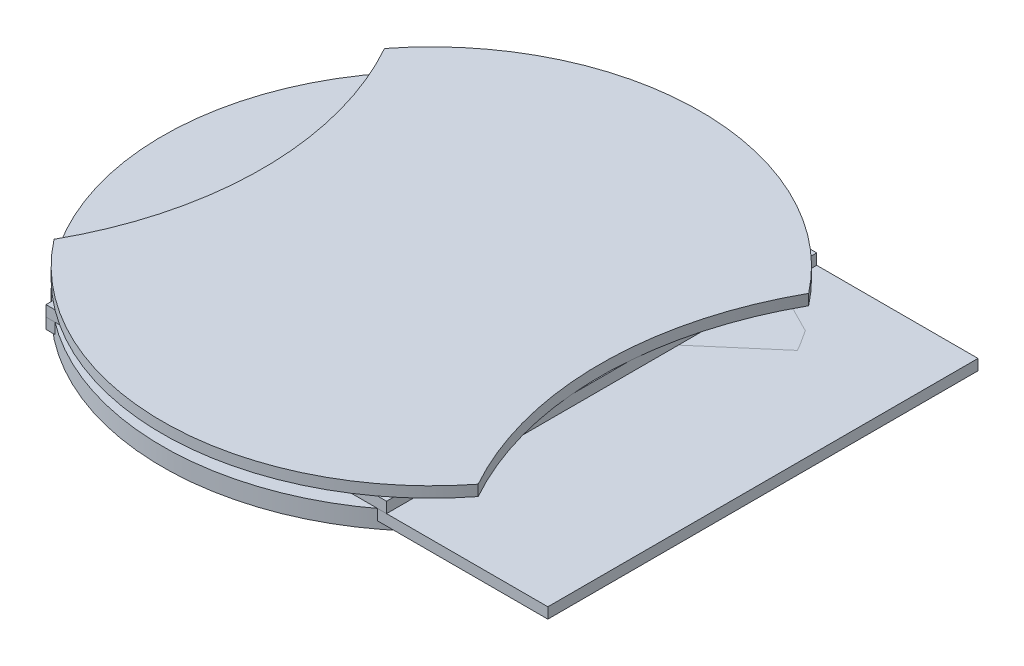
SolidWorks part; units mm, degrees
other "Markup1"
sketch "Sketch33" plane through (-11.66, 9, -138.7946) normal (0, 1, 0) x (1, 0, 0)
other "Markup2"
sketch "Sketch43" plane through (-27.5, 9, 15) normal (-0.0208, 0.9953, 0.0943) x (0.8809, -0.0263, 0.4725)
material "PMMA"
ref_plane "Front Plane" through (0, 0, 0) normal (0, 0, 1) x (1, 0, 0)
ref_plane "Top Plane" through (0, 0, 0) normal (0, 1, 0) x (1, 0, 0)
ref_plane "Right Plane" through (0, 0, 0) normal (1, 0, 0) x (0, 0, -1)
sketch "Sketch1" plane through (0, 0, 0) normal (0, 1, 0) x (1, 0, 0)
  line L1 (0, 0) -> (140, 0)
  line L2 (0, 0) -> (0, 120)
  line L3 (0, 120) -> (140, 120)
  line L4 (140, 0) -> (140, 120)
  dimension "D1" = 120
  dimension "D2" = 140
extrude "Compact" add sketch "Sketch1" along normal blind 3
sketch "Center Guide" plane through (0, 0, 0) normal (-1, 0, 0) x (0, 0, 1)
  line L0 (-60, 0) -> (-60, -3) construction
  line L1 (-120, 0) -> (0, 0) construction
  line L2 (-60, 3) -> (-60, 16.3)
  line L3 (-120, 3) -> (0, 3) construction
  line L4 (-60, 3) -> (-60, 24.5)
  circle A0 centre (-60, -3) radius 10.0584
  circle A1 centre (-60, 16.3) radius 5.9898
  circle A2 centre (-60, 24.5) radius 8.3651
  dimension "D2" = 13.3
  dimension "D3" = 21.5
  dimension "D1" = 3
sketch "Sketch4" plane through (0, 3, 0) normal (0, 1, 0) x (1, 0, 0)
  line L0 (0, 0) -> (140, 0) construction
  line L1 (0, 120) -> (95, 120)
  line L2 (0, 120) -> (0, 0)
  line L3 (0, 0) -> (95, 0)
  line L4 (95, 120) -> (95, 0)
  dimension "D1" = 95
extrude "SuperCompact" add sketch "Sketch4" along normal blind 3 separate body
sketch "Sketch5" plane through (0, 6, 0) normal (0, 1, 0) x (1, 0, 0)
  line L0 (47.5, 120) -> (47.5, 103.0921) construction
  line L1 (95, 120) -> (0, 120) construction
  line L2 (0, 60) -> (21.8037, 60) construction
  line L3 (0, 120) -> (0, 0) construction
  line L4 (70, 120) -> (70, 93.0513) construction
  line L5 (140, 120) -> (0, 120) construction
  circle A0 centre (5, 115) radius 1.5
  circle A1 centre (90, 115) radius 1.5
  circle A2 centre (90, 5) radius 1.5
  circle A3 centre (5, 5) radius 1.5
  circle A4 centre (135, 5) radius 1.5
  circle A5 centre (135, 115) radius 1.5
  dimension "D1" = 3
  dimension "D2" = 5
  dimension "D3" = 5
sketch "Sketch7" plane through (0, 6, 0) normal (0, 1, 0) x (1, 0, 0)
  line L0 (47.5, 120) -> (47.5, 0) construction
  line L1 (95, 120) -> (0, 120) construction
  line L2 (0, 0) -> (95, 0) construction
  circle A0 centre (47.5, 60) radius 75
  dimension "D1" = 150
extrude "Apple Base" add sketch "Sketch7" along normal blind 3 separate body
sketch "Sketch8" plane through (0, 9, 0) normal (0, 1, 0) x (1, 0, 0)
  line L1 (0, 120) -> (0, 0) construction
  line L2 (0, 100.6202) -> (0, 77.7186) construction
  line L3 (47.5, 135) -> (47.5, 108.0988) construction
  line L7 (-27.5, 60) -> (-27.5, 91.6393) construction
  arc A1 (-11.66, 106.0987) -> (-11.66, 13.9013) centre (-94.1268, 60) cw
  circle A2 centre (47.5, 60) radius 75 construction
  circle A3 centre (47.5, 60) radius 75
  arc A4 (-11.66, 106.0987) -> (-11.66, 13.9013) centre (47.5, 60) ccw
  arc A5 (106.66, 106.0987) -> (106.66, 13.9013) centre (189.1268, 60) ccw
  arc A6 (106.66, 106.0987) -> (106.66, 13.9013) centre (47.5, 60) cw
  dimension "D2" = 0
extrude "SideCuts" cut sketch "Sketch8" against normal through all
sketch "Sketch9" plane through (0, 6, 0) normal (0, -1, 0) x (1, 0, 0)
  arc A4 (106.66, -13.9013) -> (-11.66, -13.9013) centre (47.5, -60) ccw
  arc A5 (-11.66, -106.0987) -> (-11.66, -13.9013) centre (-94.1268, -60) ccw
  arc A6 (-11.66, -106.0987) -> (106.66, -106.0987) centre (47.5, -60) ccw
  arc A7 (106.66, -13.9013) -> (106.66, -106.0987) centre (189.1268, -60) ccw
  arc A8 (106.66, -13.9013) -> (-11.66, -13.9013) centre (47.5, -60) ccw
  arc A9 (-11.66, -106.0987) -> (-11.66, -13.9013) centre (-94.1268, -60) ccw
  arc A10 (-11.66, -106.0987) -> (106.66, -106.0987) centre (47.5, -60) ccw
  arc A11 (106.66, -13.9013) -> (106.66, -106.0987) centre (189.1268, -60) ccw
  dimension "D1" = 0
extrude "Apple_Base" add sketch "Sketch9" along normal blind 3 separate body
sketch "Sketch10" plane through (0, 6, 0) normal (0, 1, 0) x (1, 0, 0)
  line L0 (-11.66, 106.0987) -> (-11.66, 13.9013)
  line L1 (106.66, 106.0987) -> (106.66, 13.9013)
  arc A4 (106.66, 106.0987) -> (106.66, 13.9013) centre (189.1268, 60) ccw
  arc A5 (106.66, 106.0987) -> (-11.66, 106.0987) centre (47.5, 60) ccw
  arc A6 (-11.66, 13.9013) -> (-11.66, 106.0987) centre (-94.1268, 60) ccw
  arc A7 (-11.66, 13.9013) -> (106.66, 13.9013) centre (47.5, 60) ccw
  arc A8 (106.66, 106.0987) -> (106.66, 13.9013) centre (189.1268, 60) ccw
  arc A10 (-11.66, 13.9013) -> (-11.66, 106.0987) centre (-94.1268, 60) ccw
  dimension "D1" = 0
extrude "Boss-Extrude4" add sketch "Sketch10" against normal blind 3
sketch "Sketch11" plane through (0, 0, 0) normal (0, 0, 1) x (1, 0, 0)
  line L0 (-11.66, 6) -> (106.66, 6)
  line L1 (47.5, 6) -> (47.5, 18.0317)
fillet "Base_Plate_Fillet" radius 0.001 12 edges at (106.66, 6, -60) (106.66, 3, -60) (-11.66, 6, -60) (-11.66, 3, -60) (47.5, 6, -135) (47.5, 3, -135) (47.5, 6, 15) (47.5, 3, 15) (106.66, 4.5, -106.0987) (-11.66, 4.5, -106.0987) (-11.66, 4.5, -13.9013) (106.66, 4.5, -13.9013)
sketch "Sketch12" plane through (0, 6, 0) normal (0, 1, 0) x (1, 0, 0)
  line L0 (-11.659, 106.0984) -> (-11.659, 13.9016) construction
  line L1 (106.659, 13.9016) -> (106.659, 106.0984) construction
  line L2 (-4.6496, 43.9016) -> (-4.6496, 76.9016) construction
  line L3 (47.5, 134.999) -> (47.5, 105.9694) construction
  circle A0 centre (-4.6496, 43.9016) radius 2.5
  circle A1 centre (-4.6496, 76.9016) radius 2.5
  arc A2 (106.659, 106.0984) -> (-11.659, 106.0984) centre (47.5, 60) ccw construction
  circle A6 centre (99.659, 75.8016) radius 2.5
  circle A7 centre (99.659, 42.8016) radius 2.5
  dimension "D3" = 5
  dimension "D5" = 5
  dimension "D1" = 30
  dimension "D2" = 7.0094
  dimension "D4" = 33
  dimension "D6" = 33
  dimension "D7" = 28.9
  dimension "D8" = 7
extrude "Base_Screw_Holes" [suppressed] cut sketch "Sketch12" against normal blind 14
sketch "Old_Motor_Mounts" plane through (0, 6, 0) normal (0, 1, 0) x (1, 0, 0)
  line L0 (3.341, 134.7458) -> (3.341, -10.3072) construction
  line L1 (47.5, 134.999) -> (47.5, -14.999) construction
  line L2 (-11.659, 106.0984) -> (-11.659, 13.9016) construction
  line L3 (7.341, 70.6984) -> (7.341, 106.6984)
  line L4 (3.341, 70.6984) -> (3.341, 106.6984)
  line L5 (3.341, 106.6984) -> (7.341, 106.6984)
  line L6 (3.341, 70.6984) -> (7.341, 70.6984)
  line L11 (47.5, 60) -> (73.1154, 60) construction
  line L12 (91.659, 49.3016) -> (87.16, 49.4734)
  line L13 (87.16, 49.4734) -> (87.6619, 13.4542)
  line L14 (91.659, 13.3016) -> (87.6619, 13.4542)
  line L15 (91.659, 49.3016) -> (91.659, 13.3016)
  line L16 (106.659, 13.9016) -> (106.659, 106.0984) construction
  arc A0 (106.659, 106.0984) -> (-11.659, 106.0984) centre (47.5, 60) ccw construction
  arc A1 (-11.659, 13.9016) -> (106.659, 13.9016) centre (47.5, 60) ccw construction
  point P12 (3.341, 88.6984)
  point P16 (91.659, 31.3016)
  dimension "D1" = 15
  dimension "D2" = 17.4
  dimension "D3" = 36
  dimension "D5" = 36
  dimension "D6" = 15
  dimension "D7" = 4
  dimension "D8" = 17.4
  dimension "D4" = 4
ref_plane "MidPlane" through (0, 0, -60) normal (0, 0, 1) x (1, 0, 0)
sketch "Sketch24" plane through (0, 6, 0) normal (0, 1, 0) x (1, 0, 0)
  line L0 (-3.66, 114.8421) -> (-3.66, 5.1579)
  line L2 (-11.66, 13.9016) -> (-11.66, 106.0984) construction
  line L3 (47.5, 134.999) -> (47.5, 105.1076) construction
  line L4 (98.66, 114.8421) -> (98.66, 5.1579)
  line L5 (106.66, 106.0984) -> (106.66, 13.9016) construction
  line L6 (106.66, 106.0984) -> (106.66, 13.9016)
  line L7 (-11.66, 13.9016) -> (-11.66, 106.0984)
  arc A0 (106.659, 106.0984) -> (-11.659, 106.0984) centre (47.5, 60) ccw construction
  arc A1 (-11.6598, 106.099) -> (-11.66, 106.0984) centre (-11.659, 106.0984) ccw construction
  arc A2 (106.6598, 106.099) -> (-11.6598, 106.099) centre (47.5, 60) ccw construction
  arc A3 (106.66, 106.0984) -> (106.6598, 106.099) centre (106.659, 106.0984) ccw construction
  arc A4 (106.6598, 13.901) -> (106.66, 13.9016) centre (106.659, 13.9016) ccw construction
  arc A5 (-11.6598, 13.901) -> (106.6598, 13.901) centre (47.5, 60) ccw construction
  arc A6 (-11.66, 13.9016) -> (-11.6598, 13.901) centre (-11.659, 13.9016) ccw construction
  arc A7 (-11.6598, 106.099) -> (-11.66, 106.0984) centre (-11.659, 106.0984) ccw
  arc A8 (106.6598, 106.099) -> (98.66, 114.8421) centre (47.5, 60) ccw
  arc A9 (106.66, 106.0984) -> (106.6598, 106.099) centre (106.659, 106.0984) ccw
  arc A10 (106.6598, 13.901) -> (106.66, 13.9016) centre (106.659, 13.9016) ccw
  arc A11 (-11.6598, 13.901) -> (-3.66, 5.1579) centre (47.5, 60) ccw
  arc A12 (-11.66, 13.9016) -> (-11.6598, 13.901) centre (-11.659, 13.9016) ccw
  arc A13 (98.66, 5.1579) -> (106.6598, 13.901) centre (47.5, 60) ccw
  arc A14 (-3.66, 114.8421) -> (-11.6598, 106.099) centre (47.5, 60) ccw
  dimension "D1" = 8
  dimension "D2" = 8
extrude "Cut-Extrude3" [suppressed] cut sketch "Sketch24" against normal blind 6
sketch "Sketch25" plane through (0, 6, 0) normal (0, 1, 0) x (1, 0, 0)
  line L0 (-11.659, 106.0974) -> (-11.659, 111.0974)
  line L1 (47.5, 135) -> (47.5, 124.3332) construction
  line L2 (106.659, 106.0974) -> (106.659, 111.0974)
  line L3 (-11.66, 60) -> (55.4784, 60) construction
  line L4 (-11.66, 13.9016) -> (-11.66, 106.0984) construction
  line L5 (106.659, 13.9026) -> (106.659, 8.9026)
  line L6 (-11.659, 13.9026) -> (-11.659, 8.9026)
  arc A0 (-11.6598, 106.099) -> (-11.66, 106.0984) centre (-11.659, 106.0984) ccw construction
  arc A1 (106.6598, 106.099) -> (-11.6598, 106.099) centre (47.5, 60) ccw construction
  arc A2 (-11.659, 111.0974) -> (106.659, 111.0974) centre (47.5, 61.7666) cw
  arc A3 (-11.659, 106.0974) -> (106.659, 106.0974) centre (47.5, 56.7666) cw
  arc A4 (-11.659, 13.9026) -> (106.659, 13.9026) centre (47.5, 63.2334) ccw
  arc A5 (-11.659, 8.9026) -> (106.659, 8.9026) centre (47.5, 58.2334) ccw
  arc M15 (106.659, 106.0984) -> (-11.659, 106.0984) centre (47.5, 60) ccw
  arc M17 (-11.659, 13.9016) -> (106.659, 13.9016) centre (47.5, 60) ccw
  dimension "D1" = 5
extrude "Top Bottom extensions" add sketch "Sketch25" against normal blind 3 contours L6 A5 L5 A4 M17 | L0 A3 L2 A2 M15
sketch "Sketch28" plane through (0, 6, 0) normal (0, 1, 0) x (1, 0, 0)
  line L0 (-11.659, 60) -> (106.659, 60) construction
  line L1 (37.5, 6) -> (57.5, 6) construction
  line L2 (37.5, 6) -> (37.5, -14) construction
  line L3 (37.5, -14) -> (57.5, -14) construction
  line L4 (57.5, 6) -> (57.5, -14) construction
  line L5 (-11.659, 106.0984) -> (-11.659, 13.9016) construction
  line L6 (106.659, 13.9016) -> (106.659, 106.0984) construction
  line L7 (47.5, 6) -> (47.5, -4) construction
  line L8 (47.5, -4) -> (37.5, -4) construction
  circle A0 centre (41.5, 2) radius 1.75
  circle A1 centre (41.5, -10) radius 1.75
  circle A2 centre (53.5, -10) radius 1.75
  circle A3 centre (53.5, 2) radius 1.75
  circle A4 centre (53.5, 130) radius 1.75
  circle A5 centre (53.5, 118) radius 1.75
  circle A6 centre (41.5, 118) radius 1.75
  circle A7 centre (41.5, 130) radius 1.75
  point P30 (47.5, 60)
  dimension "D4" = 3.5
  dimension "D1" = 20
  dimension "D2" = 20
  dimension "D3" = 54
  dimension "D5" = 4
  dimension "D6" = 4
extrude "RodHolder holes" [suppressed] cut sketch "Sketch28" against normal blind 11
sketch "Sketch29" plane through (0, 6, 0) normal (0, 1, 0) x (1, 0, 0)
  line L0 (47.5, 138.7946) -> (47.5, -18.7946) construction
  line L5 (47.5, 60) -> (59.8359, 60) construction
  line L7 (11.25, 7.85) -> (83.75, 7.85) construction
  line L8 (11.25, 7.85) -> (11.25, 112.15) construction
  line L9 (11.25, 112.15) -> (83.75, 112.15) construction
  line L10 (83.75, 7.85) -> (83.75, 112.15) construction
  line L11 (11.25, 7.85) -> (83.75, 112.15) construction
  line L12 (11.25, 112.15) -> (83.75, 7.85) construction
  arc A5 (106.659, 111.0974) -> (-11.659, 111.0974) centre (47.5, 61.7666) ccw construction
  arc A6 (-11.659, 8.9026) -> (106.659, 8.9026) centre (47.5, 58.2334) ccw construction
  circle A7 centre (11.25, 112.15) radius 1.5
  circle A8 centre (83.75, 112.15) radius 1.5
  circle A9 centre (83.75, 7.85) radius 1.5
  circle A10 centre (11.25, 7.85) radius 1.5
  point P9 (47.5, 60)
  dimension "D1" = 104.3
  dimension "D3" = 3
  dimension "D2" = 72.5
extrude "Height extender holes" [suppressed] cut sketch "Sketch29" against normal blind 10
sketch "Sketch31" plane through (0, 6, 0) normal (0, 1, 0) x (1, 0, 0)
  line L0 (-11.659, 60) -> (106.659, 60) construction
  line L1 (-11.659, 106.0984) -> (-11.659, 13.9016) construction
  line L2 (106.659, 13.9016) -> (106.659, 106.0984) construction
  line L3 (47.5, 138.7946) -> (47.5, -18.7946) construction
  line L4 (47.5, 112) -> (72.8768, 112) construction
  arc A0 (106.659, 111.0974) -> (-11.659, 111.0974) centre (47.5, 61.7666) ccw construction
  arc A1 (-11.659, 8.9026) -> (106.659, 8.9026) centre (47.5, 58.2334) ccw construction
  circle A2 centre (47.5, 122) radius 10
  circle A3 centre (47.5, 122) radius 8
  circle A4 centre (47.5, 122) radius 15
  dimension "D1" = 20
  dimension "D3" = 2
  dimension "D4" = 30
  dimension "D2" = 52
sketch "Sketch34" plane through (0, 3, 0) normal (0, -1, 0) x (-1, 0, 0)
  line L0 (-47.5, -18.7946) -> (-47.5, 138.7946) construction
  arc A0 (-106.659, 8.9026) -> (11.659, 8.9026) centre (-47.5, 58.2334) ccw construction
  arc A1 (11.659, 111.0974) -> (-106.659, 111.0974) centre (-47.5, 61.7666) ccw construction
  circle A2 centre (-47.5, 60) radius 12.859
sketch "Sketch35" plane through (0, 3, 0) normal (0, -1, 0) x (1, 0, 0)
  line L0 (47.5, 18.7946) -> (47.5, -138.7946) construction
  line L1 (6.25, -114.85) -> (88.75, -114.85) construction
  line L2 (47.5, -60) -> (61.5955, -60) construction
  line L3 (7.5, -3.9) -> (7.5, -116.1) construction
  line L4 (6.25, -5.15) -> (86.25, -5.15) construction
  line L5 (87.5, -3.9) -> (87.5, -116.1) construction
  line L6 (7.5, 18.7946) -> (7.5, -138.7946) construction
  line L7 (87.5, 18.7946) -> (87.5, -138.7946) construction
  arc A0 (106.659, -8.9026) -> (-11.659, -8.9026) centre (47.5, -58.2334) ccw construction
  arc A1 (-11.659, -111.0974) -> (106.659, -111.0974) centre (47.5, -61.7666) ccw construction
  circle A2 centre (7.5, -5.15) radius 1.25
  circle A3 centre (87.5, -5.15) radius 1.25
  circle A4 centre (87.5, -114.85) radius 1.25
  circle A5 centre (7.5, -114.85) radius 1.25
  dimension "D1" = 40
  dimension "D3" = 2.5
  dimension "D4" = 80
  dimension "D5" = 112.2
  dimension "D2" = 40
extrude "SpacerHoles" cut sketch "Sketch35" against normal blind 10
sketch "Sketch37" plane through (0, 3, 0) normal (0, -1, 0) x (1, 0, 0)
sketch "Sketch38" plane through (0, 3, 0) normal (0, -1, 0) x (1, 0, 0)
  line L0 (-11.659, -60) -> (-6.659, -60)
  line L1 (-11.659, -13.9016) -> (-11.659, -106.0984) construction
  line L2 (-6.659, -60) -> (-6.659, 24.7024)
  line L3 (101.659, -60) -> (106.659, -60)
  line L4 (106.659, -106.0984) -> (106.659, -13.9016) construction
  line L5 (-6.659, 24.7024) -> (101.659, 24.7024)
  line L6 (101.659, 24.7024) -> (101.659, -143.8435)
  line L7 (101.659, -143.8435) -> (-6.659, -143.8435)
  line L8 (-6.659, -143.8435) -> (-6.659, -60)
  line L9 (47.5, 37.0501) -> (120.3723, 37.0501)
  line L10 (120.3723, 37.0501) -> (120.3723, -158.6018)
  line L11 (120.3723, -158.6018) -> (-29.1775, -158.6018)
  line L12 (-29.1775, -158.6018) -> (-29.1775, 37.0501)
  line L13 (-29.1775, 37.0501) -> (47.5, 37.0501)
  line M7 (106.659, -106.0984) -> (106.659, -13.9016)
  line M8 (106.659, -13.9016) -> (106.659, -8.9026)
  arc M9 (106.659, -8.9026) -> (-11.659, -8.9026) centre (47.5, -58.2334) ccw
  line M10 (-11.659, -8.9026) -> (-11.659, -13.9016)
  line M11 (-11.659, -13.9016) -> (-11.659, -106.0984)
  line M12 (-11.659, -106.0984) -> (-11.659, -111.0974)
  arc M13 (-11.659, -111.0974) -> (106.659, -111.0974) centre (47.5, -61.7666) ccw
  line M14 (106.659, -111.0974) -> (106.659, -106.0984)
  dimension "D1" = 5
  dimension "D2" = 5
extrude "Cut-Extrude4" cut sketch "Sketch38" against normal blind 10 contours L13 L12 L11 L10 L9 L7 L8 L2 L5 L6 M13 M12 M11 M10 M9 M8 M7 M14 | L6 L3 M9 M7 M8 | L0 L2 M9 M10 M11 | L8 L0 M13 M11 M12 | L3 L6 M13 M14 M7
sketch "Sketch39" plane through (0, 3, 0) normal (0, -1, 0) x (1, 0, 0)
  line L0 (47.5, 18.7946) -> (47.5, -81.8228) construction
  line L2 (101.659, -60) -> (38.5892, -60) construction
  line L3 (101.659, -3.4601) -> (101.659, -116.5399) construction
  arc A1 (101.659, -3.4601) -> (-6.659, -3.4601) centre (47.5, -58.2334) ccw construction
  circle A2 centre (47.5, -60) radius 75
  circle A3 centre (87.5, -5.15) radius 1.25
  circle A4 centre (7.5, -5.15) radius 1.25
  circle A5 centre (7.5, -114.85) radius 1.25
  circle A6 centre (87.5, -114.85) radius 1.25
  dimension "D1" = 150
extrude "Boss-Extrude5" add sketch "Sketch39" along normal blind 5
sketch "Sketch40" plane through (101.659, 0, 0) normal (1, 0, 0) x (0, 0, -1)
  line L0 (3.4601, 3) -> (-22.7338, 3)
  line L1 (-22.7338, 3) -> (-22.7338, 8.214)
  line L2 (-22.7338, 8.214) -> (147.503, 8.214)
  line L3 (147.503, 8.214) -> (147.503, 3)
  line L4 (147.503, 3) -> (3.4601, 3)
extrude "Cut-Extrude5" cut sketch "Sketch40" against normal blind 150
sketch "Sketch41" plane through (0, 3, 0) normal (0, 1, 0) x (1, 0, 0)
  line L0 (47.5, 60) -> (97.5, 60)
  circle A3 centre (47.5, 60) radius 8.5
  circle A4 centre (97.5, 60) radius 8.5
  dimension "D2" = 50
  dimension "D6" = 17
  dimension "D4" = 17
extrude "Cut-Extrude6" cut sketch "Sketch41" against normal blind 10
sketch "Sketch44" plane through (0, 3, 0) normal (0, 1, 0) x (1, 0, 0)
  line L0 (47.5, 60) -> (107.5, 60)
  circle A0 centre (107.5, 60) radius 8.5
  dimension "D2" = 17
  dimension "D1" = 60
extrude "Cut-Extrude7" cut sketch "Sketch44" against normal blind 10
